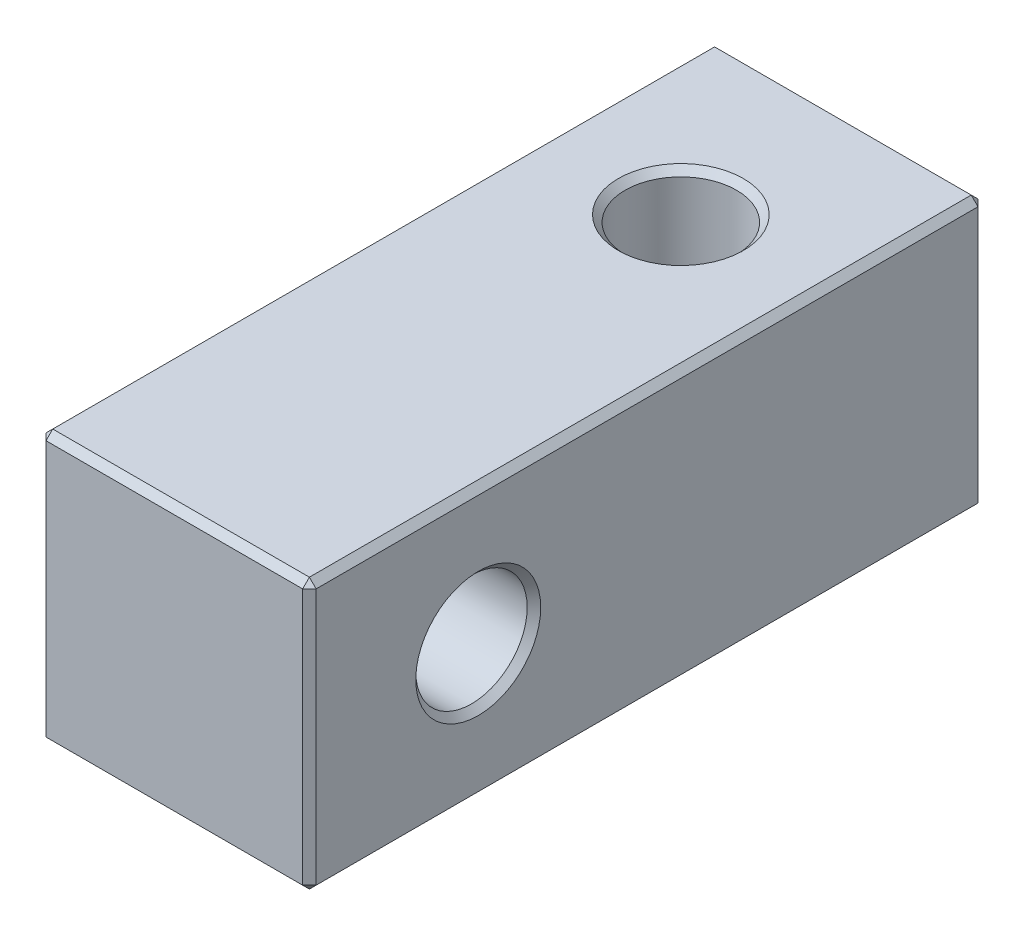
SolidWorks part; units mm, degrees
ref_plane "前视基准面" through (0, 0, 0) normal (0, 0, 1) x (1, 0, 0)
ref_plane "上视基准面" through (0, 0, 0) normal (0, 1, 0) x (1, 0, 0)
ref_plane "右视基准面" through (0, 0, 0) normal (1, 0, 0) x (0, 0, -1)
sketch "草图1" plane through (0, 0, 0) normal (0, 0, 1) x (1, 0, 0)
  line L1 (-4, 4) -> (4, 4)
  line L2 (-4, 4) -> (-4, -4)
  line L3 (-4, -4) -> (4, -4)
  line L4 (4, 4) -> (4, -4)
  line L5 (-4, 4) -> (4, -4) construction
  line L6 (-4, -4) -> (4, 4) construction
  point P0 (0, 0)
  dimension "D1" = 8
extrude "凸台-拉伸1" add sketch "草图1" along normal mid plane 20
hole_wizard "M4 螺纹孔1" positions "草图2" profile "草图3" tap size "M4" standard "GB" end condition through all
sketch "草图2" plane through (4, 0, 0) normal (1, 0, 0) x (0, 0, -1)
  line L0 (0, 0) -> (50000, 0) construction
  line L1 (10, -4) -> (10, 4) construction
  point P0 (-5, 0)
  point P7 (0, 0)
  dimension "D1" = 15
sketch "草图3" plane through (4, 0, 5) normal (0, 1, 0) x (0, 0, -1)
  line L0 (0, 0) -> (0, 8)
  line L1 (0, 8) -> (1.65, 8)
  line L2 (1.65, 8) -> (1.65, 0)
  line L5 (1.65, 0) -> (0, 0)
  line L11 (0, -6.35) -> (0, 107.95) construction
  dimension "通孔螺纹孔钻头直径" = 3.3
  dimension "通孔螺纹孔钻头深度" = 8
cosmetic thread "孔螺蚊线1" parameters "D2"=4
hole_wizard "M4 螺纹孔2" positions "草图4" profile "草图5" tap size "M4" standard "GB" end condition through all
sketch "草图4" plane through (0, 4, 0) normal (0, 1, 0) x (1, 0, 0)
  line L0 (4, -10) -> (-4, -10) construction
  line L1 (0, 0) -> (0, 50000) construction
  point P0 (0, 5)
  point P8 (0, 0)
  dimension "D1" = 15
sketch "草图5" plane through (0, 4, -5) normal (1, 0, 0) x (0, 0, 1)
  line L0 (0, 0) -> (0, 8)
  line L1 (0, 8) -> (1.65, 8)
  line L2 (1.65, 8) -> (1.65, 0)
  line L5 (1.65, 0) -> (0, 0)
  line L11 (0, -6.35) -> (0, 107.95) construction
  dimension "通孔螺纹孔钻头直径" = 3.3
  dimension "通孔螺纹孔钻头深度" = 8
cosmetic thread "孔螺蚊线2"
chamfer "倒角1" distance 0.2 angle 45 16 edges at (0, -4, -3.35) (-4, 0, 3.35) (0, 4, -3.35) (0, -4, 10) (0, -4, -10) (-4, 0, 10) (-4, -4, 0) (-4, 0, -10) (0, 4, 10) (-4, 4, 0) (0, 4, -10) (4, -4, 0) (4, 0, 10) (4, 4, 0) (4, 0, -10) (4, 0, 3.35)
